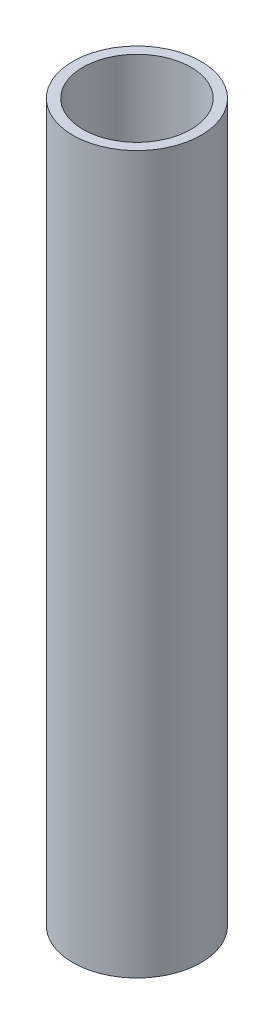
SolidWorks part; units mm, degrees
ref_plane "Front Plane" through (0, 0, 0) normal (0, 0, 1) x (1, 0, 0)
ref_plane "Top Plane" through (0, 0, 0) normal (0, 1, 0) x (1, 0, 0)
ref_plane "Right Plane" through (0, 0, 0) normal (1, 0, 0) x (0, 0, -1)
sketch "Sketch1" plane through (0, 0, 0) normal (0, 1, 0) x (1, 0, 0)
  circle A0 centre (0, 0) radius 25.4
  circle A1 centre (0, 0) radius 30.1625
  dimension "D1" = 50.8
  dimension "D2" = 60.325
extrude "Boss-Extrude1" add sketch "Sketch1" along normal mid plane 337.312
